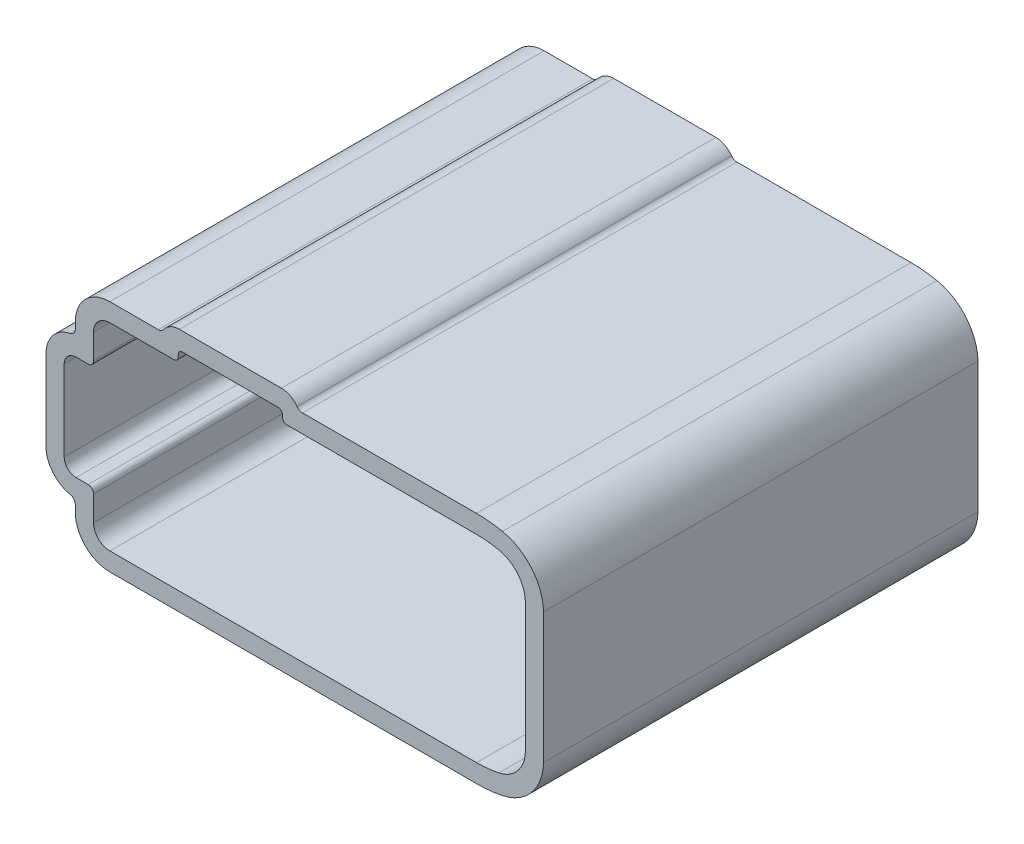
SolidWorks part; units mm, degrees
ref_plane "Front Plane" through (0, 0, 0) normal (0, 0, 1) x (1, 0, 0)
ref_plane "Top Plane" through (0, 0, 0) normal (0, 1, 0) x (1, 0, 0)
ref_plane "Right Plane" through (0, 0, 0) normal (1, 0, 0) x (0, 0, -1)
sketch "Sketch1" plane through (0, 0, 0) normal (0, 0, 1) x (1, 0, 0)
  line L0 (1.016, -5.461) -> (2.413, -5.461) construction
  line L1 (3.429, -4.445) -> (3.429, -1.524) construction
  line L3 (4.953, 0) -> (13.335, 0) construction
  line L4 (53.1635, -3.5809) -> (53.1635, -18.7711) construction
  line L5 (0, -6.477) -> (0, -15.875) construction
  line L6 (0, -11.176) -> (53.1635, -11.176) construction
  line L7 (24.765, 0) -> (47.8309, 0) construction
  line L8 (4.953, -22.352) -> (47.8309, -22.352) construction
  line L9 (3.429, -17.907) -> (3.429, -20.828) construction
  line L10 (1.016, -16.891) -> (2.413, -16.891) construction
  line L11 (13.335, 0) -> (13.335, 1.27) construction
  line L12 (13.335, 1.27) -> (24.765, 1.27) construction
  line L13 (24.765, 1.27) -> (24.765, 0) construction
  line L26 (0, -11.684) -> (53.1635, -11.684)
  line L27 (12.954, 0.889) -> (12.954, 1.143)
  line L28 (13.462, 1.651) -> (24.638, 1.651)
  line L29 (25.146, 1.143) -> (25.146, 0.889)
  line L30 (25.654, 0.381) -> (47.8309, 0.381)
  line L31 (53.5445, -3.5755) -> (53.5445, -18.7765)
  line L32 (4.953, -22.733) -> (47.8309, -22.733)
  line L33 (0.921, -2.9543) -> (0.921, -1.524)
  line L34 (4.953, 2.508) -> (11.0531, 2.508)
  line L35 (3.048, -17.907) -> (3.048, -20.828)
  line L36 (13.081, 3.778) -> (25.019, 3.778)
  line L37 (1.016, -17.272) -> (2.413, -17.272)
  line L38 (27.0469, 2.508) -> (47.8309, 2.508)
  line L39 (55.6715, -3.5495) -> (55.6715, -18.8025)
  line L40 (4.953, -24.86) -> (47.8309, -24.86)
  line L41 (0.921, -19.3977) -> (0.921, -20.828)
  line L42 (-0.381, -6.477) -> (-0.381, -15.875)
  line L43 (-2.508, -6.477) -> (-2.508, -15.875)
  line L44 (1.016, -5.08) -> (2.413, -5.08)
  line L45 (3.048, -4.445) -> (3.048, -1.524)
  line L46 (4.953, 0.381) -> (12.446, 0.381)
  line L47 (12.954, 0.381) -> (12.954, 1.651) construction
  line L48 (4.953, 0.381) -> (12.954, 0.381) construction
  line L49 (12.954, 1.651) -> (25.146, 1.651) construction
  line L50 (25.146, 1.651) -> (25.146, 0.381) construction
  line L51 (25.146, 0.381) -> (47.8309, 0.381) construction
  arc A0 (2.413, -5.461) -> (3.429, -4.445) centre (2.413, -4.445) ccw construction
  arc A1 (1.016, -5.461) -> (0, -6.477) centre (1.016, -6.477) ccw construction
  arc A2 (50.3664, -22.0963) -> (53.1635, -18.7711) centre (49.6683, -18.6701) ccw construction
  arc A3 (3.429, -1.524) -> (4.953, 0) centre (4.953, -1.524) cw construction
  arc A4 (47.8309, 0) -> (50.3664, -0.2557) centre (47.8309, -12.7) cw construction
  arc A5 (47.8309, -22.352) -> (50.3664, -22.0963) centre (47.8309, -9.652) ccw construction
  arc A6 (3.429, -20.828) -> (4.953, -22.352) centre (4.953, -20.828) ccw construction
  arc A7 (50.3664, -0.2557) -> (53.1635, -3.5809) centre (49.6683, -3.6819) cw construction
  arc A8 (1.016, -16.891) -> (0, -15.875) centre (1.016, -15.875) cw construction
  arc A9 (2.413, -16.891) -> (3.429, -17.907) centre (2.413, -17.907) cw construction
  arc A24 (47.8309, 0.381) -> (50.4425, 0.1177) centre (47.8309, -12.7) cw
  arc A25 (0.921, -1.524) -> (4.953, 2.508) centre (4.953, -1.524) cw
  arc A26 (50.4425, 0.1177) -> (53.5445, -3.5755) centre (49.6683, -3.6819) cw
  arc A27 (11.0531, 2.508) -> (13.081, 3.778) centre (13.081, 1.524) cw
  arc A28 (25.019, 3.778) -> (27.0469, 2.508) centre (25.019, 1.524) cw
  arc A29 (50.4425, -22.4697) -> (53.5445, -18.7765) centre (49.6683, -18.6701) ccw
  arc A30 (47.8309, 2.508) -> (50.8671, 2.2018) centre (47.8309, -12.7) cw
  arc A31 (50.8671, 2.2018) -> (55.6715, -3.5495) centre (49.6683, -3.6819) cw
  arc A32 (50.8671, -24.5538) -> (55.6715, -18.8025) centre (49.6683, -18.6701) ccw
  arc A33 (47.8309, -24.86) -> (50.8671, -24.5538) centre (47.8309, -9.652) ccw
  arc A34 (0.921, -20.828) -> (4.953, -24.86) centre (4.953, -20.828) ccw
  arc A35 (47.8309, -22.733) -> (50.4425, -22.4697) centre (47.8309, -9.652) ccw
  arc A36 (0.921, -19.3977) -> (-2.508, -15.875) centre (1.016, -15.875) cw
  arc A37 (0.921, -2.9543) -> (-2.508, -6.477) centre (1.016, -6.477) ccw
  arc A38 (3.048, -20.828) -> (4.953, -22.733) centre (4.953, -20.828) ccw
  arc A39 (2.413, -17.272) -> (3.048, -17.907) centre (2.413, -17.907) cw
  arc A40 (1.016, -17.272) -> (-0.381, -15.875) centre (1.016, -15.875) cw
  arc A41 (1.016, -5.08) -> (-0.381, -6.477) centre (1.016, -6.477) ccw
  arc A42 (2.413, -5.08) -> (3.048, -4.445) centre (2.413, -4.445) ccw
  arc A43 (3.048, -1.524) -> (4.953, 0.381) centre (4.953, -1.524) cw
  arc A44 (12.954, 0.889) -> (12.446, 0.381) centre (12.446, 0.889) cw
  arc A45 (12.954, 1.143) -> (13.462, 1.651) centre (13.462, 1.143) cw
  arc A46 (24.638, 1.651) -> (25.146, 1.143) centre (24.638, 1.143) cw
  arc A47 (25.146, 0.889) -> (25.654, 0.381) centre (25.654, 0.889) ccw
  point P12 (13.335, 0)
  point P19 (49.911, 0)
  point P27 (24.765, 0)
  point P35 (49.911, -22.352)
  dimension "D7" = 1.016
  dimension "D8" = 0.381
  dimension "D9" = 12.7
  dimension "D10" = 0.508
  dimension "D1" = 8.382
  dimension "D2" = 3.429
  dimension "D3" = 19.812
  dimension "D4" = 5.715
  dimension "D5" = 1.27
  dimension "D6" = 0.508
extrude "Boss-Extrude1" add sketch "Sketch1" along normal blind 50.8
fillet "Fillet1" radius 0.762 4 edges at (27.0469, 2.508, 25.4) (11.0531, 2.508, 25.4) (0.921, -2.9543, 25.4) (0.921, -19.3977, 25.4)
